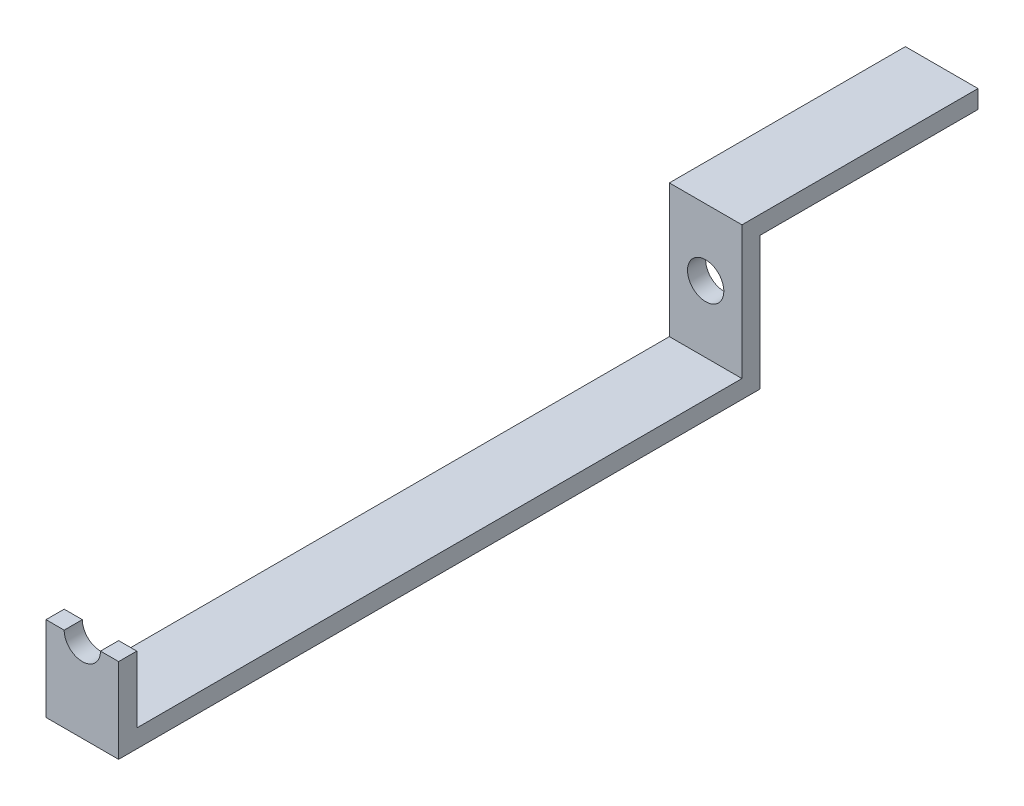
SolidWorks part; units mm, degrees
ref_plane "前视基准面" through (0, 0, 0) normal (0, 0, 1) x (1, 0, 0)
ref_plane "上视基准面" through (0, 0, 0) normal (0, 1, 0) x (1, 0, 0)
ref_plane "右视基准面" through (0, 0, 0) normal (1, 0, 0) x (0, 0, -1)
sketch "草图2" plane through (0, 0, 0) normal (1, 0, 0) x (0, 0, -1)
  line L0 (0, 16.5) -> (0, -15.5769) construction
  line L1 (-53, 0) -> (53, 0)
  line L2 (53, 0) -> (53, 20)
  line L4 (50, 20) -> (50, 3)
  line L5 (50, 3) -> (-50, 3)
  line L6 (50, 20) -> (50, 25)
  line L7 (-50, 14) -> (-50, 3)
  line L8 (-53, 0) -> (-53, 14)
  line L9 (-53, 14) -> (-50, 14)
  line L10 (50, 25) -> (89, 25)
  line L11 (89, 25) -> (89, 22)
  line L12 (89, 22) -> (53, 22)
  line L13 (53, 22) -> (53, 20)
  point P10 (0, 3)
  point P13 (0, 0)
  dimension "D1" = 3
  dimension "D2" = 20
  dimension "D3" = 3
  dimension "D4" = 53
  dimension "D5" = 14
  dimension "D6" = 2
  dimension "D7" = 3
  dimension "D8" = 36
extrude "凸台-拉伸1" add sketch "草图2" along normal blind 12
sketch "草图3" plane through (0, 0, -53) normal (0, 0, -1) x (-1, 0, 0)
  line L0 (-6, 22) -> (-6, 0) construction
  line L2 (-12, 0) -> (0, 0) construction
  line L3 (-12, 22) -> (0, 22) construction
  circle A0 centre (-6, 14) radius 3
  point P12 (-6, 21.5971)
  dimension "D1" = 6
  dimension "D2" = 8
extrude "切除-拉伸1" cut sketch "草图3" against normal up to surface (106 mm away) up to face at (6, 7, 53)
